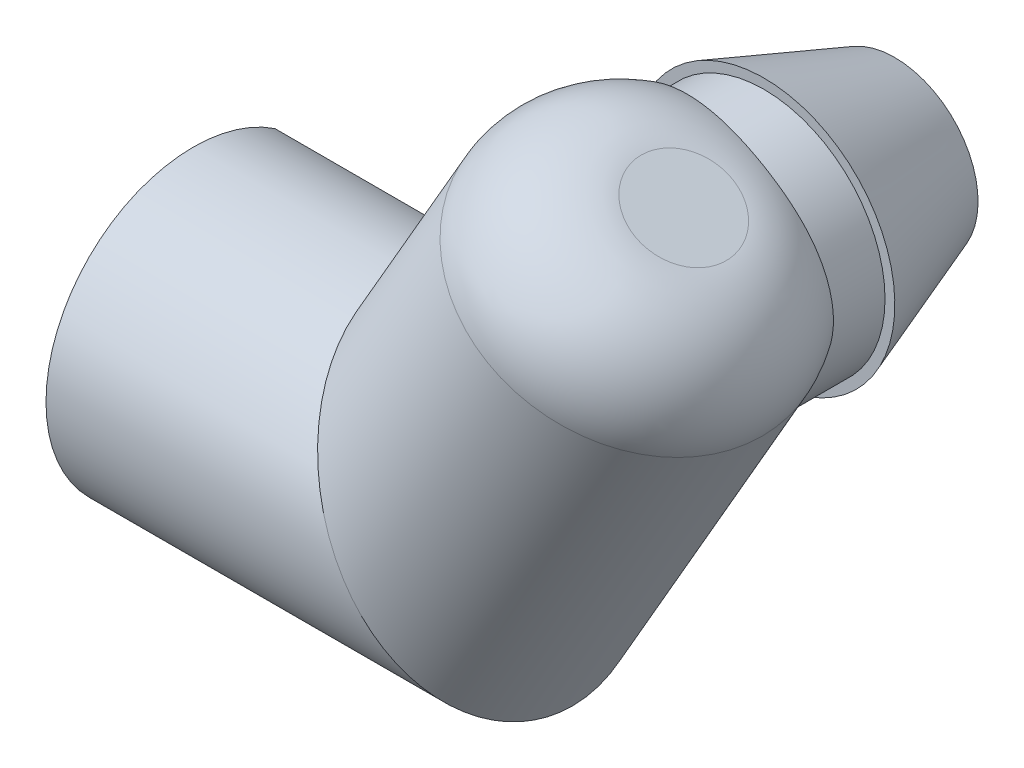
SolidWorks part; units mm, degrees
ref_plane "Front Plane" through (0, 0, 0) normal (0, 0, 1) x (1, 0, 0)
ref_plane "Top Plane" through (0, 0, 0) normal (0, 1, 0) x (1, 0, 0)
ref_plane "Right Plane" through (0, 0, 0) normal (1, 0, 0) x (0, 0, -1)
sketch "Sketch2" plane through (0, 0, 0) normal (0, 0, 1) x (1, 0, 0)
  line L0 (-4.5, 0) -> (0, 0) construction
  line L1 (0, 0) -> (3, 5.1962) construction
  line L2 (-4.5, 0) -> (0, 0)
  line L3 (0, 0) -> (3, 5.1962)
  dimension "D1" = 4.5
  dimension "D2" = 6
  dimension "D3" = 120
ref_plane "Plane1" through (-4.5, 0, 0) normal (1, 0, 0) x (0, 0, -1)
sketch "Sketch3" plane through (-4.5, 0, 0) normal (1, 0, 0) x (0, 0, -1)
  circle A0 centre (0, 0) radius 2.25
  dimension "D1" = 4.5
sweep "Sweep1" add profiles "Sketch3" path "Sketch2"
fillet "Fillet2" radius 1.5 1 edges at (3, 5.1962, -2.25)
sketch "Sketch4" plane through (-4.5, 0, 0) normal (-1, 0, 0) x (0, 0, 1)
  circle A0 centre (0, 0) radius 1.125
  dimension "D1" = 2.25
sketch "Sketch5" plane through (0, 0, 0) normal (0, 0, 1) x (1, 0, 0)
  line L0 (-4.5, 0) -> (1.2, 0)
  line L1 (-4.5, 1.125) -> (-4.5, -1.125) construction
  dimension "D1" = 5.7
sweep "Cut-Sweep1" cut profiles "Sketch4" path "Sketch5"
ref_plane "Plane2" through (0, 0, -1.25) normal (0, 0, 1) x (1, 0, 0)
sketch "Sketch6" plane through (0, 0, -1.25) normal (0, 0, 1) x (1, 0, 0)
  line L9 (-4.6679, 5.8534) -> (4.6291, 5.8534)
  line L10 (-4.6679, 5.8534) -> (-4.6679, -2.403)
  line L11 (-4.6679, -2.403) -> (4.6291, -2.403)
  line L12 (4.6291, 5.8534) -> (4.6291, -2.403)
extrude "Cut-Extrude1" cut sketch "Sketch6" against normal blind 3
sketch "Sketch7" plane through (0, 0, -1.25) normal (0, 0, -1) x (-1, 0, 0)
  line L0 (-3, 5.1962) -> (0, 0) construction
  line L1 (-2.3505, 5.5712) -> (-3.6495, 4.8212) construction
  line L2 (0, 0) -> (4.5, 0) construction
  line L3 (4.5, 1.8708) -> (4.5, -1.8708) construction
  circle A0 centre (-1.7774, 3.0786) radius 1.85
  dimension "D1" = 3.7
extrude "Boss-Extrude2" add sketch "Sketch7" along normal blind 1.2
sketch "Sketch8" plane through (0, 0, -2.45) normal (0, 0, -1) x (-1, 0, 0)
  circle A0 centre (-1.7774, 3.0786) radius 2
  circle A1 centre (-1.7774, 3.0786) radius 1.85 construction
  dimension "D1" = 4
extrude "Boss-Extrude3" add sketch "Sketch8" along normal blind 2 draft 20
sketch "Sketch9" plane through (0, 0, -4.45) normal (0, 0, -1) x (-1, 0, 0)
  circle A0 centre (-1.7774, 3.0786) radius 0.85
  circle A1 centre (-1.7774, 3.0786) radius 1.2721 construction
  dimension "D1" = 1.7
extrude "Cut-Extrude2" cut sketch "Sketch9" against normal blind 2.4
sketch "Sketch10" plane through (0, 0, -4.45) normal (0, 0, -1) x (-1, 0, 0)
  line L1 (-1.1013, 3.4666) -> (0.4341, 3.4666)
  line L2 (-1.1013, 3.4666) -> (-1.1013, 2.7666)
  line L3 (-1.1013, 2.7666) -> (0.4341, 2.7666)
  line L4 (0.4341, 3.4666) -> (0.4341, 2.7666)
  dimension "D1" = 0.7
extrude "Cut-Extrude3" cut sketch "Sketch10" against normal blind 2.4
ref_plane "Plane3" [suppressed] through (0, 0, -10) normal (0, 0, 1) x (1, 0, 0)
mirror "Mirror1" [suppressed] about plane through (0, 0, -10) normal (0, 0, 1)
delete or keep bodies "Body-Delete/Keep 1" [suppressed] type delete bodies bodies 109
